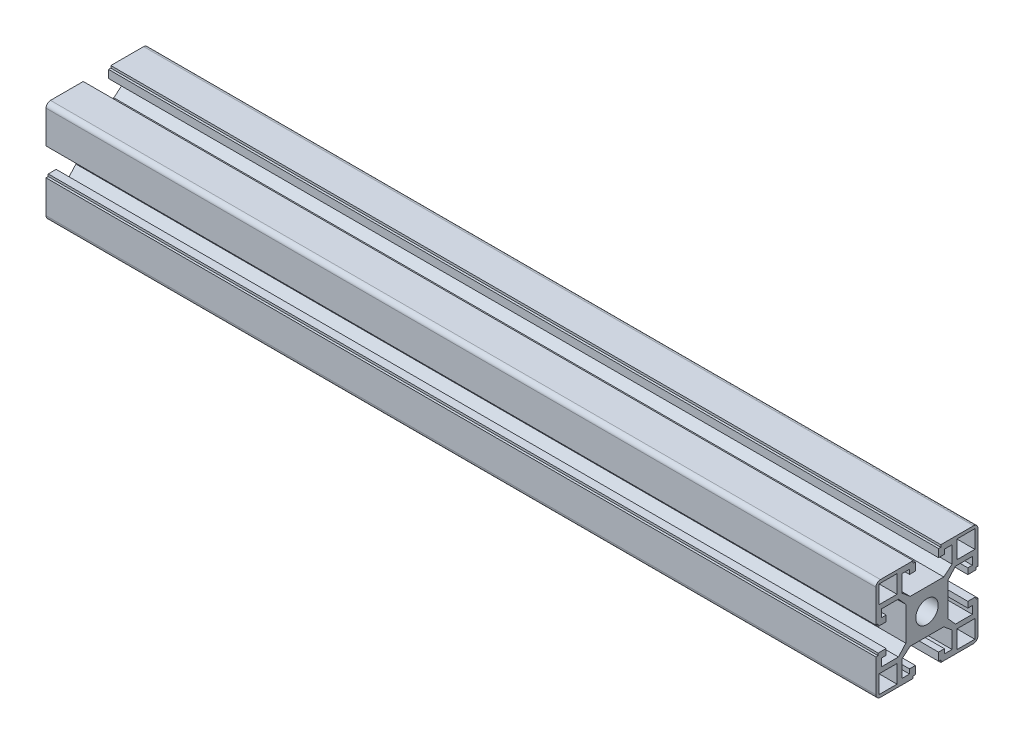
SolidWorks part; units mm, degrees
ref_plane "前视基准面" through (0, 0, 0) normal (0, 0, 1) x (1, 0, 0)
ref_plane "上视基准面" through (0, 0, 0) normal (0, 1, 0) x (1, 0, 0)
ref_plane "右视基准面" through (0, 0, 0) normal (1, 0, 0) x (0, 0, -1)
other "Configuration Table"
sketch "草图1" plane through (0, 0, 0) normal (1, 0, 0) x (0, 0, -1)
  line L1 (15.205, 55.0358) -> (60.705, 55.0358)
  line L2 (15.205, 55.0358) -> (15.205, 9.5358)
  line L3 (15.205, 9.5358) -> (60.705, 9.5358)
  line L4 (60.705, 55.0358) -> (60.705, 9.5358)
  dimension "D1" = 45.5
  dimension "D2" = 45.5
extrude "凸台-拉伸1" add sketch "草图1" along normal blind 370
sketch "草图2" plane through (370, 0, 0) normal (1, 0, 0) x (0, 0, -1)
  line L0 (37.955, 55.0358) -> (37.955, 9.5358) construction
  line L3 (60.705, 55.0358) -> (15.205, 55.0358) construction
  line L90 (15.205, 9.5358) -> (60.705, 9.5358) construction
  line L91 (15.205, 32.2858) -> (60.705, 32.2858) construction
  line L92 (15.205, 55.0358) -> (15.205, 9.5358) construction
  line L93 (60.705, 9.5358) -> (60.705, 55.0358) construction
  line L94 (31.805, 55.0358) -> (31.805, 54.0358)
  line L95 (16.605, 53.6358) -> (24.605, 53.6358)
  line L96 (16.605, 53.6358) -> (16.605, 45.6358)
  line L97 (16.605, 45.6358) -> (24.605, 45.6358)
  line L98 (24.605, 53.6358) -> (24.605, 45.6358)
  line L99 (31.805, 54.0358) -> (32.805, 54.0358)
  line L100 (32.805, 54.0358) -> (32.805, 50.5058)
  line L101 (32.805, 50.5058) -> (30.175, 50.5058)
  line L102 (30.175, 50.5058) -> (30.175, 52.5058)
  line L103 (30.175, 52.5058) -> (26.775, 52.5058)
  line L104 (26.775, 52.5058) -> (26.775, 45.0058)
  line L105 (26.775, 45.0058) -> (30.455, 41.9058)
  line L106 (30.455, 41.9058) -> (37.955, 41.9058)
  line L107 (37.955, 41.9058) -> (37.955, 55.0358)
  line L108 (37.955, 55.0358) -> (31.805, 55.0358)
  dimension "D14" = 1
  dimension "D1" = 8
  dimension "D2" = 8
  dimension "D3" = 1.4
  dimension "D4" = 1.4
  dimension "D5" = 5.15
  dimension "D6" = 1
  dimension "D7" = 3.53
  dimension "D8" = 2.63
  dimension "D9" = 2
  dimension "D10" = 3.4
  dimension "D11" = 7.5
  dimension "D12" = 8.6
  dimension "D13" = 7.5
extrude "切除-拉伸1" cut sketch "草图2" against normal up to next
ref_plane "基准面1" through (0, 0, -37.955) normal (0, 0, -1) x (-1, 0, 0)
ref_plane "基准面2" through (0, 32.2858, 0) normal (0, -1, 0) x (-1, 0, 0)
mirror "镜向1" about plane through (0, 0, -37.955) normal (0, 0, -1) of "切除-拉伸1"
mirror "镜向2" about plane through (0, 32.2858, 0) normal (0, -1, 0) of "镜向1", "切除-拉伸1"
sketch "草图3" plane through (370, 0, 0) normal (1, 0, 0) x (0, 0, -1)
  line L0 (15.205, 38.4358) -> (16.205, 38.4358)
  line L1 (15.205, 55.0358) -> (15.205, 9.5358) construction
  line L2 (16.205, 38.4358) -> (16.205, 37.4358)
  line L3 (16.205, 37.4358) -> (19.735, 37.4358)
  line L4 (19.735, 37.4358) -> (19.735, 40.0658)
  line L5 (19.735, 40.0658) -> (17.735, 40.0658)
  line L6 (17.735, 40.0658) -> (17.735, 43.4658)
  line L7 (17.735, 43.4658) -> (25.235, 43.4658)
  line L8 (25.235, 43.4658) -> (28.535, 39.7858)
  line L9 (28.535, 39.7858) -> (28.535, 32.2858)
  line L10 (-9.13, 32.2858) -> (9.13, 32.2858) construction
  line L11 (28.535, 32.2858) -> (15.205, 32.2858)
  line L12 (15.205, 32.2858) -> (15.205, 38.4358)
  dimension "D1" = 1
  dimension "D2" = 1
  dimension "D3" = 5.15
  dimension "D4" = 3.53
  dimension "D5" = 2.63
  dimension "D6" = 2
  dimension "D7" = 3.4
  dimension "D8" = 7.5
  dimension "D9" = 7.5
  dimension "D10" = 8.8
extrude "切除-拉伸2" cut sketch "草图3" against normal up to next
mirror "镜向3" about plane through (0, 32.2858, 0) normal (0, -1, 0) of "切除-拉伸2"
mirror "镜向4" about plane through (0, 0, -37.955) normal (0, 0, -1) of "镜向3", "切除-拉伸2"
fillet "圆角1" radius 2 4 edges at (185, 55.0358, -15.205) (185, 9.5358, -15.205) (185, 9.5358, -60.705) (185, 55.0358, -60.705)
sketch "草图6" plane through (370, 0, 0) normal (1, 0, 0) x (0, 0, -1)
  line L0 (37.955, 41.9058) -> (37.955, 22.6658) construction
  line L1 (30.455, 41.9058) -> (45.455, 41.9058) construction
  line L2 (30.455, 22.6658) -> (45.455, 22.6658) construction
  line L3 (28.535, 32.2858) -> (47.375, 32.2858) construction
  line L4 (28.535, 24.7858) -> (28.535, 39.7858) construction
  line L5 (47.375, 39.7858) -> (47.375, 24.7858) construction
  circle A0 centre (37.955, 32.2858) radius 5
  dimension "D1" = 10
extrude "切除-拉伸4" cut sketch "草图6" against normal up to next
